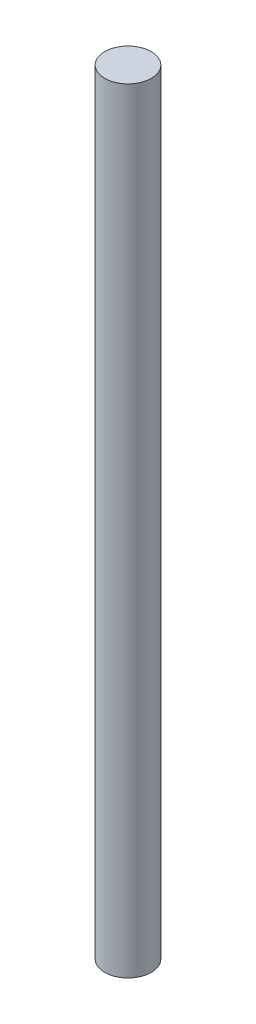
SolidWorks part; units mm, degrees
ref_plane "Front Plane" through (0, 0, 0) normal (0, 0, 1) x (1, 0, 0)
ref_plane "Top Plane" through (0, 0, 0) normal (0, 1, 0) x (1, 0, 0)
ref_plane "Right Plane" through (0, 0, 0) normal (1, 0, 0) x (0, 0, -1)
sketch "Sketch1" plane through (0, 0, 0) normal (0, 1, 0) x (1, 0, 0)
  circle A0 centre (0, 0) radius 7.5
  dimension "D1" = 15
extrude "Boss-Extrude1" add sketch "Sketch1" along normal blind 250
